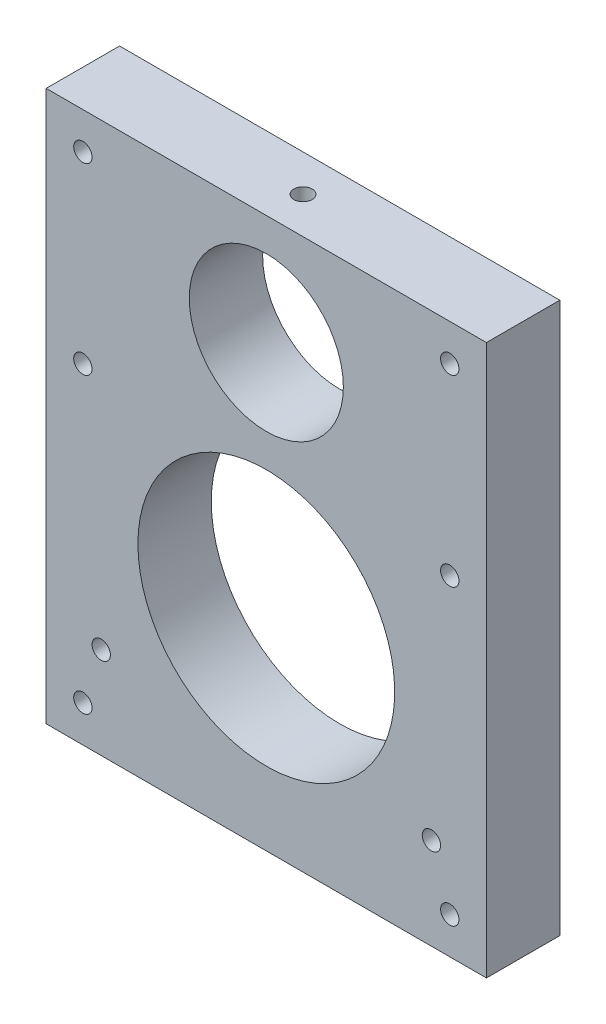
SolidWorks part; units mm, degrees
ref_plane "Front Plane" through (0, 0, 0) normal (0, 0, 1) x (1, 0, 0)
ref_plane "Top Plane" through (0, 0, 0) normal (0, 1, 0) x (1, 0, 0)
ref_plane "Right Plane" through (0, 0, 0) normal (1, 0, 0) x (0, 0, -1)
sketch "Sketch1" plane through (0, 0, 0) normal (0, 0, 1) x (1, 0, 0)
  line L1 (76.2, -95.25) -> (-76.2, -95.25)
  line L2 (76.2, -95.25) -> (76.2, 95.25)
  line L3 (76.2, 95.25) -> (-76.2, 95.25)
  line L4 (-76.2, -95.25) -> (-76.2, 95.25)
  line L5 (76.2, -95.25) -> (-76.2, 95.25) construction
  line L6 (76.2, 95.25) -> (-76.2, -95.25) construction
  point P0 (0, 0)
  dimension "D1" = 152.4
  dimension "D2" = 190.5
extrude "Boss-Extrude1" add sketch "Sketch1" along normal blind 25.4
sketch "Sketch2" plane through (0, 0, 0) normal (0, 0, -1) x (-1, 0, 0)
  circle A0 centre (0, 57.15) radius 26.67
  dimension "D1" = 53.34
extrude "Cut-Extrude1" cut sketch "Sketch2" against normal through all
sketch "Sketch3" plane through (0, 0, 0) normal (0, 0, -1) x (-1, 0, 0)
  circle A0 centre (-63.5, 82.55) radius 3.175
  circle A1 centre (63.5, 82.55) radius 3.175
  circle A2 centre (63.5, -82.55) radius 3.175
  circle A3 centre (-63.5, -82.55) radius 3.175
  dimension "D1" = 6.35
extrude "Cut-Extrude3" cut sketch "Sketch3" against normal through all both and the other way through all
sketch "Sketch4" plane through (0, 0, 0) normal (0, 0, -1) x (-1, 0, 0)
  circle A0 centre (0, -25.4) radius 44.45
  dimension "D1" = 88.9
extrude "Cut-Extrude4" cut sketch "Sketch4" against normal through all both and the other way through all
sketch "Sketch6" plane through (0, 0, 0) normal (0, 0, -1) x (-1, 0, 0)
  circle A0 centre (-63.5, 19.05) radius 3.175
  circle A1 centre (63.5, 19.05) radius 3.175
  dimension "D1" = 6.35
  dimension "D2" = 6.35
extrude "Cut-Extrude5" cut sketch "Sketch6" against normal through all both and the other way through all
sketch "Sketch7" plane through (0, 0, 0) normal (0, 0, -1) x (-1, 0, 0)
  circle A0 centre (-57.15, -63.5) radius 3.175
  circle A1 centre (57.15, -63.5) radius 3.175
  dimension "D1" = 6.35
  dimension "D2" = 6.35
extrude "Cut-Extrude6" cut sketch "Sketch7" against normal through all both and the other way through all
sketch "Sketch8" plane through (0, 95.25, 0) normal (0, 1, 0) x (1, 0, 0)
  circle A0 centre (0, -12.7) radius 3.175
extrude "Cut-Extrude7" cut sketch "Sketch8" against normal blind 25.4
